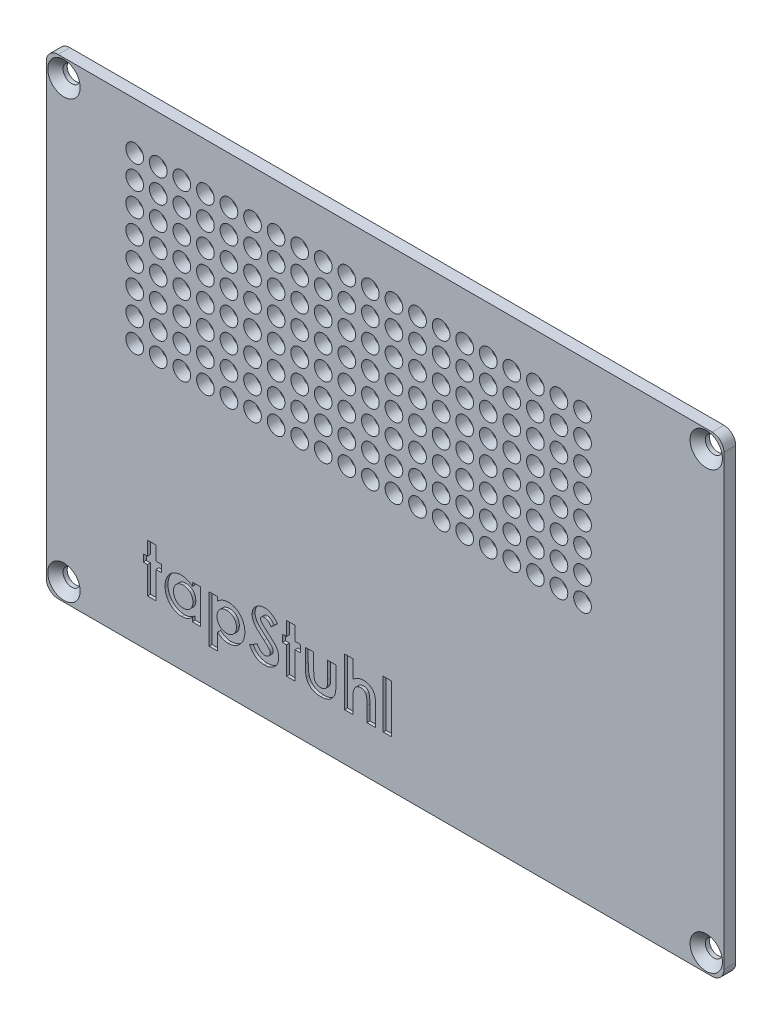
SolidWorks part; units mm, degrees
ref_plane "Ebene vorne" through (0, 0, 0) normal (0, 0, 1) x (1, 0, 0)
ref_plane "Ebene oben" through (0, 0, 0) normal (0, 1, 0) x (1, 0, 0)
ref_plane "Ebene rechts" through (0, 0, 0) normal (1, 0, 0) x (0, 0, -1)
sketch "Sketch1" plane through (0, 0, 0) normal (0, 0, 1) x (1, 0, 0)
  line L4 (113, 80) -> (2, 80)
  line L5 (0, 78) -> (0, 2)
  line L6 (2, 0) -> (113, 0)
  line L7 (115, 2) -> (115, 78)
  line L8 (113, 80) -> (2, 80)
  line L9 (0, 78) -> (0, 2)
  line L10 (2, 0) -> (113, 0)
  line L11 (115, 2) -> (115, 78)
  arc A8 (2, 80) -> (0, 78) centre (2, 78) ccw
  arc A9 (2, 80) -> (0, 78) centre (2, 78) ccw
  arc A10 (0, 2) -> (2, 0) centre (2, 2) ccw
  arc A11 (0, 2) -> (2, 0) centre (2, 2) ccw
  arc A12 (113, 0) -> (115, 2) centre (113, 2) ccw
  arc A13 (113, 0) -> (115, 2) centre (113, 2) ccw
  arc A14 (115, 78) -> (113, 80) centre (113, 78) ccw
  arc A15 (115, 78) -> (113, 80) centre (113, 78) ccw
  dimension "D1" = 0
extrude "Boss-Extrude1" add sketch "Sketch1" along normal blind 2
sketch "Sketch4" plane through (0, 0, 0) normal (0, 0, -1) x (-1, 0, 0)
  line L7 (-7.709, 75.8) -> (-106.7958, 75.8)
  line L8 (-106.7958, 75.8) -> (-110.8, 71.7958)
  line L9 (-110.8, 71.7958) -> (-110.8, 8.2042)
  line L10 (-110.8, 8.2042) -> (-106.7958, 4.2)
  line L11 (-106.7958, 4.2) -> (-8.2042, 4.2)
  line L12 (-8.2042, 4.2) -> (-4.2, 8.2042)
  line L13 (-4.2, 8.2042) -> (-4.2, 72.291)
  line L14 (-7.5231, 77.3) -> (-107.4172, 77.3)
  line L15 (-107.4172, 77.3) -> (-112.3, 72.4172)
  line L16 (-112.3, 72.4172) -> (-112.3, 7.5828)
  line L17 (-112.3, 7.5828) -> (-107.4172, 2.7)
  line L18 (-2.7, 7.5828) -> (-2.7, 72.4769)
  line L19 (-7.5828, 2.7) -> (-2.7, 7.5828)
  line L20 (-107.4172, 2.7) -> (-7.5828, 2.7)
  line L21 (-7.5231, 77.3) -> (-107.4172, 77.3)
  line L22 (-107.4172, 77.3) -> (-112.3, 72.4172)
  line L23 (-112.3, 72.4172) -> (-112.3, 7.5828)
  line L24 (-112.3, 7.5828) -> (-107.4172, 2.7)
  line L25 (-2.7, 7.5828) -> (-2.7, 72.4769)
  line L26 (-7.5828, 2.7) -> (-2.7, 7.5828)
  line L27 (-107.4172, 2.7) -> (-7.5828, 2.7)
  arc A1 (-4.2, 72.291) -> (-7.709, 75.8) centre (-9.0093, 70.9907) ccw
  arc A2 (-2.7, 72.4769) -> (-7.5231, 77.3) centre (-9.0093, 70.9907) ccw
  arc A3 (-2.7, 72.4769) -> (-7.5231, 77.3) centre (-9.0093, 70.9907) ccw
  dimension "D1" = 0.2
  dimension "D2" = 1.5
extrude "Boss-Extrude2" add sketch "Sketch4" along normal blind 1
sketch "Sketch5" plane through (0, 0, 2) normal (0, 0, 1) x (1, 0, 0)
  line L0 (0, 78) -> (0, 2) construction
  line L1 (113, 80) -> (2, 80) construction
  line L2 (15, 72) -> (19, 72) construction
  line L3 (15, 72) -> (15, 68) construction
  circle A0 centre (15, 72) radius 1.5
  circle A1 centre (19, 72) radius 1.5
  circle A2 centre (23, 72) radius 1.5
  circle A3 centre (27, 72) radius 1.5
  circle A4 centre (31, 72) radius 1.5
  circle A5 centre (35, 72) radius 1.5
  circle A6 centre (39, 72) radius 1.5
  circle A7 centre (43, 72) radius 1.5
  circle A8 centre (19, 68) radius 1.5
  circle A9 centre (23, 68) radius 1.5
  circle A10 centre (27, 68) radius 1.5
  circle A11 centre (31, 68) radius 1.5
  circle A12 centre (35, 68) radius 1.5
  circle A13 centre (39, 68) radius 1.5
  circle A14 centre (43, 68) radius 1.5
  circle A15 centre (19, 64) radius 1.5
  circle A16 centre (23, 64) radius 1.5
  circle A17 centre (27, 64) radius 1.5
  circle A18 centre (31, 64) radius 1.5
  circle A19 centre (35, 64) radius 1.5
  circle A20 centre (39, 64) radius 1.5
  circle A21 centre (43, 64) radius 1.5
  circle A22 centre (19, 60) radius 1.5
  circle A23 centre (23, 60) radius 1.5
  circle A24 centre (27, 60) radius 1.5
  circle A25 centre (31, 60) radius 1.5
  circle A26 centre (35, 60) radius 1.5
  circle A27 centre (39, 60) radius 1.5
  circle A28 centre (43, 60) radius 1.5
  circle A29 centre (15, 68) radius 1.5
  circle A30 centre (15, 64) radius 1.5
  circle A31 centre (15, 60) radius 1.5
  circle A40 centre (15, 56) radius 1.5
  circle A41 centre (19, 56) radius 1.5
  circle A42 centre (23, 56) radius 1.5
  circle A43 centre (27, 56) radius 1.5
  circle A44 centre (31, 56) radius 1.5
  circle A45 centre (35, 56) radius 1.5
  circle A46 centre (39, 56) radius 1.5
  circle A47 centre (43, 56) radius 1.5
  circle A50 centre (15, 52) radius 1.5
  circle A51 centre (19, 52) radius 1.5
  circle A52 centre (23, 52) radius 1.5
  circle A53 centre (27, 52) radius 1.5
  circle A54 centre (31, 52) radius 1.5
  circle A55 centre (35, 52) radius 1.5
  circle A56 centre (39, 52) radius 1.5
  circle A57 centre (43, 52) radius 1.5
  circle A60 centre (15, 48) radius 1.5
  circle A61 centre (19, 48) radius 1.5
  circle A62 centre (23, 48) radius 1.5
  circle A63 centre (27, 48) radius 1.5
  circle A64 centre (31, 48) radius 1.5
  circle A65 centre (35, 48) radius 1.5
  circle A66 centre (39, 48) radius 1.5
  circle A67 centre (43, 48) radius 1.5
  circle A68 centre (47, 72) radius 1.5
  circle A69 centre (51, 72) radius 1.5
  circle A70 centre (47, 68) radius 1.5
  circle A71 centre (51, 68) radius 1.5
  circle A72 centre (47, 64) radius 1.5
  circle A73 centre (51, 64) radius 1.5
  circle A74 centre (47, 60) radius 1.5
  circle A75 centre (51, 60) radius 1.5
  circle A76 centre (47, 56) radius 1.5
  circle A77 centre (51, 56) radius 1.5
  circle A78 centre (47, 52) radius 1.5
  circle A79 centre (51, 52) radius 1.5
  circle A80 centre (47, 48) radius 1.5
  circle A81 centre (51, 48) radius 1.5
  circle A82 centre (55, 72) radius 1.5
  circle A83 centre (59, 72) radius 1.5
  circle A84 centre (63, 72) radius 1.5
  circle A85 centre (67, 72) radius 1.5
  circle A86 centre (71, 72) radius 1.5
  circle A87 centre (75, 72) radius 1.5
  circle A88 centre (79, 72) radius 1.5
  circle A89 centre (83, 72) radius 1.5
  circle A90 centre (87, 72) radius 1.5
  circle A91 centre (91, 72) radius 1.5
  circle A92 centre (55, 68) radius 1.5
  circle A93 centre (59, 68) radius 1.5
  circle A94 centre (63, 68) radius 1.5
  circle A95 centre (67, 68) radius 1.5
  circle A96 centre (71, 68) radius 1.5
  circle A97 centre (75, 68) radius 1.5
  circle A98 centre (79, 68) radius 1.5
  circle A99 centre (83, 68) radius 1.5
  circle A100 centre (87, 68) radius 1.5
  circle A101 centre (91, 68) radius 1.5
  circle A102 centre (55, 64) radius 1.5
  circle A103 centre (59, 64) radius 1.5
  circle A104 centre (63, 64) radius 1.5
  circle A105 centre (67, 64) radius 1.5
  circle A106 centre (71, 64) radius 1.5
  circle A107 centre (75, 64) radius 1.5
  circle A108 centre (79, 64) radius 1.5
  circle A109 centre (83, 64) radius 1.5
  circle A110 centre (87, 64) radius 1.5
  circle A111 centre (91, 64) radius 1.5
  circle A112 centre (55, 60) radius 1.5
  circle A113 centre (59, 60) radius 1.5
  circle A114 centre (63, 60) radius 1.5
  circle A115 centre (67, 60) radius 1.5
  circle A116 centre (71, 60) radius 1.5
  circle A117 centre (75, 60) radius 1.5
  circle A118 centre (79, 60) radius 1.5
  circle A119 centre (83, 60) radius 1.5
  circle A120 centre (87, 60) radius 1.5
  circle A121 centre (91, 60) radius 1.5
  circle A122 centre (55, 56) radius 1.5
  circle A123 centre (59, 56) radius 1.5
  circle A124 centre (63, 56) radius 1.5
  circle A125 centre (67, 56) radius 1.5
  circle A126 centre (71, 56) radius 1.5
  circle A127 centre (75, 56) radius 1.5
  circle A128 centre (79, 56) radius 1.5
  circle A129 centre (83, 56) radius 1.5
  circle A130 centre (87, 56) radius 1.5
  circle A131 centre (91, 56) radius 1.5
  circle A132 centre (55, 52) radius 1.5
  circle A133 centre (59, 52) radius 1.5
  circle A134 centre (63, 52) radius 1.5
  circle A135 centre (67, 52) radius 1.5
  circle A136 centre (71, 52) radius 1.5
  circle A137 centre (75, 52) radius 1.5
  circle A138 centre (79, 52) radius 1.5
  circle A139 centre (83, 52) radius 1.5
  circle A140 centre (87, 52) radius 1.5
  circle A141 centre (91, 52) radius 1.5
  circle A142 centre (55, 48) radius 1.5
  circle A143 centre (59, 48) radius 1.5
  circle A144 centre (63, 48) radius 1.5
  circle A145 centre (67, 48) radius 1.5
  circle A146 centre (71, 48) radius 1.5
  circle A147 centre (75, 48) radius 1.5
  circle A148 centre (79, 48) radius 1.5
  circle A149 centre (83, 48) radius 1.5
  circle A150 centre (87, 48) radius 1.5
  circle A151 centre (91, 48) radius 1.5
  circle A152 centre (15, 44) radius 1.5
  circle A153 centre (19, 44) radius 1.5
  circle A154 centre (23, 44) radius 1.5
  circle A155 centre (27, 44) radius 1.5
  circle A156 centre (31, 44) radius 1.5
  circle A157 centre (35, 44) radius 1.5
  circle A158 centre (39, 44) radius 1.5
  circle A159 centre (43, 44) radius 1.5
  circle A160 centre (47, 44) radius 1.5
  circle A161 centre (51, 44) radius 1.5
  circle A162 centre (55, 44) radius 1.5
  circle A163 centre (59, 44) radius 1.5
  circle A164 centre (63, 44) radius 1.5
  circle A165 centre (67, 44) radius 1.5
  circle A166 centre (71, 44) radius 1.5
  circle A167 centre (75, 44) radius 1.5
  circle A168 centre (79, 44) radius 1.5
  circle A169 centre (83, 44) radius 1.5
  circle A170 centre (87, 44) radius 1.5
  circle A171 centre (91, 44) radius 1.5
  dimension "D1" = 3
  dimension "D2" = 15
  dimension "D3" = 8
  dimension "D6" = 4
  dimension "D7" = 4
  dimension "D4" = 20
  dimension "D5" = 8
extrude "Cut-Extrude1" cut sketch "Sketch5" against normal through all
sketch "Sketch7" plane through (0, 0, 2) normal (0, 0, 1) x (1, 0, 0)
  circle A0 centre (3, 77) radius 1.15 construction
  circle A1 centre (3, 3) radius 1.15 construction
  circle A2 centre (112, 77) radius 1.15 construction
  circle A3 centre (112, 3) radius 1.15 construction
  point P0 (112, 77)
  point P1 (3, 77)
  point P3 (3, 3)
  point P4 (112, 3)
hole_wizard "CSK for M2.5 Countersunk Flat Head Screw1" positions "Sketch10" profile "Sketch11" countersink size "M2.5" standard "DIN" end condition up to next
sketch "Sketch10" plane through (0, 0, 2) normal (0, 0, 1) x (1, 0, 0)
  point P0 (3, 77)
  point P3 (3, 3)
  point P6 (112, 3)
  point P9 (112, 77)
sketch "Sketch11" plane through (3, 77, 2) normal (1, 0, 0) x (0, -1, 0)
  line L0 (0, 0) -> (0, 2)
  line L1 (0, 2) -> (1.45, 2)
  line L2 (1.45, 2) -> (1.45, 1.3)
  line L3 (1.45, 1.3) -> (2.75, 0)
  line L5 (2.75, 0) -> (0, 0)
  line L6 (-1.45, 1.3) -> (-2.75, 0) construction
  line L11 (0, -6.35) -> (0, 107.95) construction
  dimension "Thru Hole Dia." = 2.9
  dimension "Thru Hole Depth" = 2
  dimension "Near C'Sink Dia." = 5.5
  dimension "Near C'Sink Angle" = 90
sketch "Sketch12" plane through (0, 0, 2) normal (0, 0, 1) x (1, 0, 0)
  line L0 (16.3642, 8) -> (115, 8) construction
  line L2 (115, 2) -> (115, 78) construction
  line L3 (2, 0) -> (113, 0) construction
  line L4 (16.3642, 48.6237) -> (16.3642, 8) construction
  circle A0 centre (15, 48) radius 1.5 construction
  text T0 "tapStuhl" font "Century Gothic" height 8
  dimension "D1" = 8
extrude "Cut-Extrude2" cut sketch "Sketch12" against normal blind 0.5
